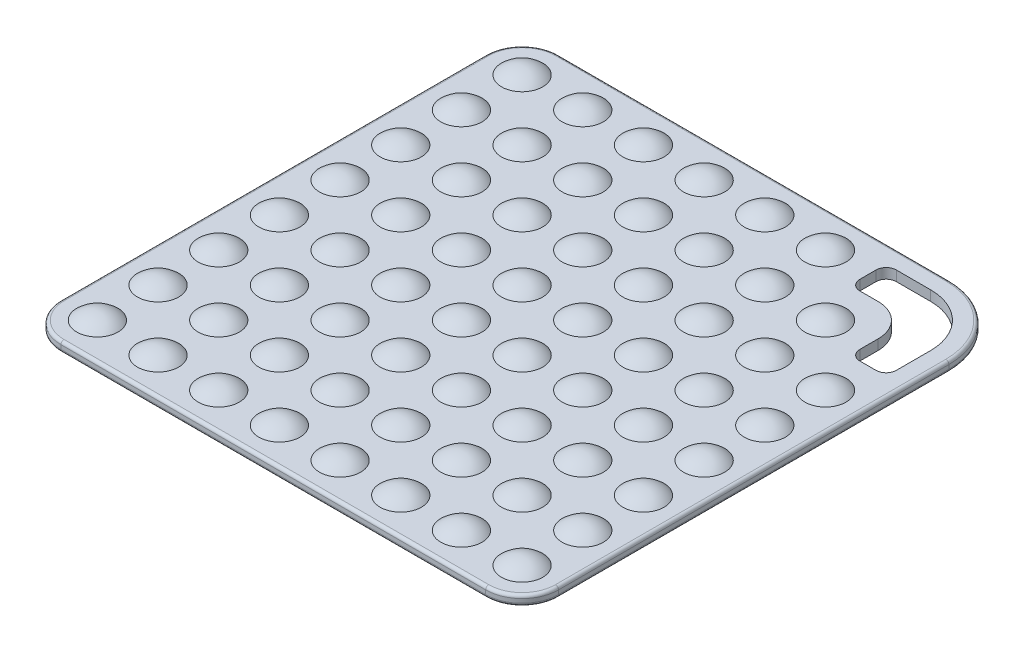
SolidWorks part; units mm, degrees
material "Rubber"
ref_plane "Front Plane" through (0, 0, 0) normal (0, 0, 1) x (1, 0, 0)
ref_plane "Top Plane" through (0, 0, 0) normal (0, 1, 0) x (1, 0, 0)
ref_plane "Right Plane" through (0, 0, 0) normal (1, 0, 0) x (0, 0, -1)
sketch "Sketch1" plane through (0, 0, 0) normal (0, 1, 0) x (1, 0, 0)
  line L1 (105, -123) -> (-105, -123)
  line L2 (123, -105) -> (123, 88)
  line L3 (88, 123) -> (-105, 123)
  line L4 (-123, -105) -> (-123, 105)
  line L5 (123, -123) -> (-123, 123) construction
  line L6 (123, 123) -> (-123, -123) construction
  line L12 (71, 114) -> (88, 114)
  line L13 (114, 88) -> (114, 71)
  line L14 (109, 66) -> (101, 66)
  line L15 (96, 71) -> (96, 80)
  line L16 (80, 96) -> (71, 96)
  line L17 (66, 101) -> (66, 109)
  arc A0 (-105, 123) -> (-123, 105) centre (-105, 105) ccw
  arc A1 (-105, -123) -> (-123, -105) centre (-105, -105) cw
  arc A2 (105, -123) -> (123, -105) centre (105, -105) ccw
  arc A3 (123, 88) -> (88, 123) centre (88, 88) ccw
  arc A11 (88, 114) -> (114, 88) centre (88, 88) cw
  arc A13 (114, 71) -> (109, 66) centre (109, 71) cw
  arc A14 (101, 66) -> (96, 71) centre (101, 71) cw
  arc A15 (71, 96) -> (66, 101) centre (71, 101) cw
  arc A16 (71, 114) -> (66, 109) centre (71, 109) ccw
  arc A17 (80, 96) -> (96, 80) centre (80, 80) cw
  point P0 (0, 0)
  point P29 (88, 66)
  point P35 (66, 88)
  dimension "D2" = 18
  dimension "D3" = 35
  dimension "D4" = 26
  dimension "D6" = 22
  dimension "D5" = 5
  dimension "D8" = 16
  dimension "D1" = 246
  dimension "D7" = 18
extrude "Boss-Extrude1" add sketch "Sketch1" along normal blind 5
ref_plane "Plane1" through (0, 0, 105) normal (0, 0, 1) x (1, 0, 0)
sketch "Sketch4" plane through (0, 0, 105) normal (0, 0, 1) x (1, 0, 0)
  line L2 (123, 2.5) -> (105, 2.5) construction
  line L3 (123, 5) -> (123, 0) construction
  line L4 (105, 5) -> (105, 0) construction
  line L5 (115.198, 5) -> (105, 5)
  line L6 (105, 5) -> (105, 9)
  line L7 (-105, 5) -> (-123, 5) construction
  arc A1 (105, 9) -> (115.198, 5) centre (105, -6) cw
  dimension "D2" = 15
  dimension "D1" = 4
revolve "Revolve2" add sketch "Sketch4" angle 360 about L6
pattern_linear "LPattern1" count 8 spacing 30 along (0, 0, -1) count 8 spacing 30 along (-1, 0, 0) skipping (6, 0), (7, 0), (7, 1) of "Revolve2"
fillet "Fillet1" radius 1.5 16 edges at (-117.7279, 0, -117.7279) (-8.5, 0, -123) (112.7487, 0, -112.7487) (123, 0, 8.5) (117.7279, 0, 117.7279) (0, 0, 123) (-117.7279, 0, 117.7279) (-8.5, 5, -123) (112.7487, 5, -112.7487) (123, 5, 8.5) (117.7279, 5, 117.7279) (0, 5, 123) (-117.7279, 5, 117.7279) (-123, 5, 0) (-123, 0, 0) (-117.7279, 5, -117.7279)
